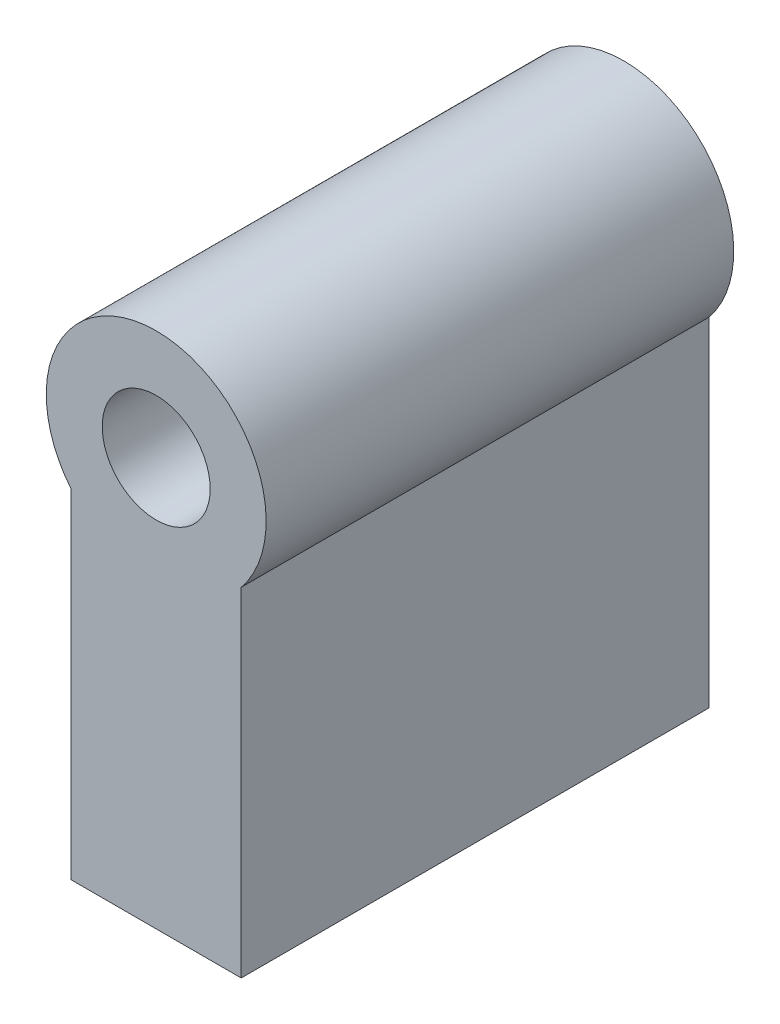
SolidWorks part; units mm, degrees
ref_plane "Alzado" through (0, 0, 0) normal (0, 0, 1) x (1, 0, 0)
ref_plane "Planta" through (0, 0, 0) normal (0, 1, 0) x (1, 0, 0)
ref_plane "Vista lateral" through (0, 0, 0) normal (1, 0, 0) x (0, 0, -1)
sketch "Croquis1" plane through (0, 0, 0) normal (0, 0, 1) x (1, 0, 0)
  line L0 (10, 0) -> (10, 13) construction
  line L1 (0, 0) -> (20, 0) construction
  line L2 (0, 0) -> (0, -35)
  line L3 (0, -35) -> (20, -35)
  line L4 (20, 0) -> (20, -35)
  line L5 (0, 0) -> (0, 4.802)
  line L6 (20, 0) -> (20, 4.802)
  arc A0 (20, 4.802) -> (0, 4.802) centre (10, 13) ccw
  dimension "D1" = 20
  dimension "D2" = 35
  dimension "D3" = 13
extrude "Saliente-Extruir1" add sketch "Croquis1" along normal blind 55
sketch "Croquis2" plane through (0, 0, 55) normal (0, 0, 1) x (1, 0, 0)
  circle A0 centre (10, 13) radius 6.35
  dimension "D1" = 12.7
extrude "Cortar-Extruir1" cut sketch "Croquis2" against normal blind 55
